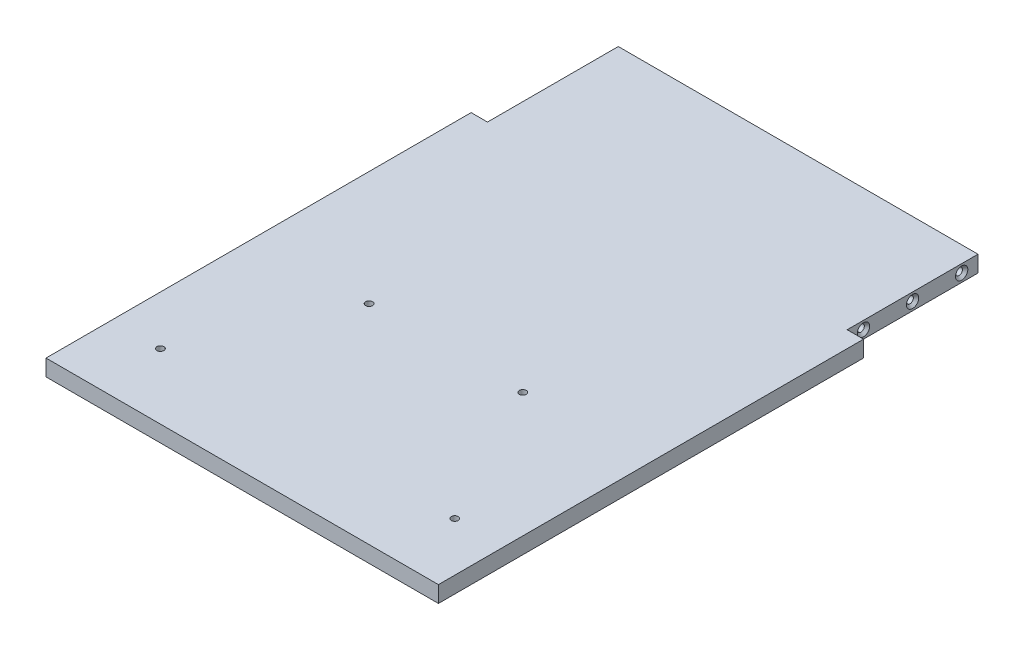
SolidWorks part; units mm, degrees
ref_plane "Front Plane" through (0, 0, 0) normal (0, 0, 1) x (1, 0, 0)
ref_plane "Top Plane" through (0, 0, 0) normal (0, 1, 0) x (1, 0, 0)
ref_plane "Right Plane" through (0, 0, 0) normal (1, 0, 0) x (0, 0, -1)
sketch "Sketch1" plane through (0, 0, 0) normal (0, 1, 0) x (1, 0, 0)
  line L0 (-6.35, 0) -> (-6.35, -50.8)
  line L1 (-6.35, 0) -> (-146.05, 0)
  line L2 (0, -50.8) -> (0, -215.9)
  line L3 (0, -215.9) -> (-152.4, -215.9)
  line L4 (-152.4, -50.8) -> (-152.4, -215.9)
  line L5 (-6.35, -50.8) -> (0, -50.8)
  line L6 (-146.05, 0) -> (-146.05, -50.8)
  line L7 (-146.05, -50.8) -> (-152.4, -50.8)
  point P7 (-3.175, -50.8)
  dimension "D1" = 152.4
  dimension "D2" = 215.9
  dimension "D3" = 50.8
  dimension "D4" = 6.35
  dimension "D5" = 6.35
  dimension "D6" = 50.8
extrude "Boss-Extrude1" add sketch "Sketch1" along normal blind 6.35
sketch "Sketch2" plane through (-6.35, 0, 0) normal (1, 0, 0) x (0, 0, -1)
  line L0 (-50.8, 6.35) -> (-50.8, 0) construction
  line L1 (-50.8, 6.35) -> (-50.8, 0) construction
  line L2 (-50.8, 0) -> (0, 0) construction
  circle A0 centre (-44.45, 3.175) radius 1.8288
  circle A1 centre (-25.4, 3.175) radius 1.8288
  circle A2 centre (-6.35, 3.175) radius 1.8288
  dimension "D4" = 3.175
  dimension "D5" = 3.175
  dimension "D6" = 3.6576
  dimension "D7" = 3.6576
  dimension "D8" = 3.6576
  dimension "D1" = 6.35
  dimension "D2" = 25.4
  dimension "D3" = 44.45
hole_wizard "#6-32 Tapped Hole1" positions "Sketch3" profile "Sketch4" tap size "#6-32" standard "ANSI Inch"
sketch "Sketch3" plane through (-6.35, 0, 0) normal (1, 0, 0) x (0, 0, -1)
  point P0 (-44.45, 3.175)
  point P3 (-25.4, 3.175)
  point P6 (-6.35, 3.175)
sketch "Sketch4" plane through (-6.35, 3.175, 44.45) normal (0, 1, 0) x (0, 0, -1)
  line L0 (0, 0) -> (0, 12.7)
  line L1 (0, 12.7) -> (1.3525, 11.8873)
  line L2 (1.3525, 11.8873) -> (1.3525, 1.0351)
  line L3 (1.3525, 1.0351) -> (2.3876, 0)
  line L5 (2.3876, 0) -> (0, 0)
  line L6 (-1.3525, 1.0351) -> (-2.3876, 0) construction
  line L10 (0, 12.7) -> (-1.3526, 11.8873) construction
  line L11 (0, -6.35) -> (0, 107.95) construction
  dimension "Tap Drill Dia." = 2.7051
  dimension "Tap Drill Depth" = 12.7
  dimension "Near C'Sink Dia." = 4.7752
  dimension "Near C'Sink Angle" = 90
  dimension "Drill Angle" = 118
cosmetic thread "Hole Thread1"
cosmetic thread "Hole Thread2"
cosmetic thread "Hole Thread3"
sketch "Sketch5" plane through (-146.05, 0, 0) normal (-1, 0, 0) x (0, 0, 1)
  circle A0 centre (6.35, 3.175) radius 1.8288
  circle A1 centre (25.4, 3.175) radius 1.8288
  circle A2 centre (44.45, 3.175) radius 1.8288
  dimension "D1" = 3.6576
  dimension "D2" = 3.6576
  dimension "D3" = 3.6576
hole_wizard "#6-32 Tapped Hole2" positions "Sketch6" profile "Sketch7" tap size "#6-32" standard "ANSI Inch"
sketch "Sketch6" plane through (-146.05, 0, 0) normal (-1, 0, 0) x (0, 0, 1)
  point P0 (6.35, 3.175)
  point P3 (25.4, 3.175)
  point P6 (44.45, 3.175)
sketch "Sketch7" plane through (-146.05, 3.175, 6.35) normal (0, 1, 0) x (0, 0, 1)
  line L0 (0, 0) -> (0, 12.7)
  line L1 (0, 12.7) -> (1.3525, 11.8873)
  line L2 (1.3525, 11.8873) -> (1.3525, 1.0351)
  line L3 (1.3525, 1.0351) -> (2.3876, 0)
  line L5 (2.3876, 0) -> (0, 0)
  line L6 (-1.3525, 1.0351) -> (-2.3876, 0) construction
  line L10 (0, 12.7) -> (-1.3526, 11.8873) construction
  line L11 (0, -6.35) -> (0, 107.95) construction
  dimension "Tap Drill Dia." = 2.7051
  dimension "Tap Drill Depth" = 12.7
  dimension "Near C'Sink Dia." = 4.7752
  dimension "Near C'Sink Angle" = 90
  dimension "Drill Angle" = 118
cosmetic thread "Hole Thread4"
cosmetic thread "Hole Thread5"
cosmetic thread "Hole Thread6"
sketch "Sketch8" plane through (0, 6.35, 0) normal (0, 1, 0) x (1, 0, 0)
  line L0 (0, -215.9) -> (0, -50.8) construction
  line L1 (-152.4, -215.9) -> (0, -215.9) construction
  circle A0 centre (-48.26, -134.874) radius 1.8288
  circle A1 centre (-107.95, -134.874) radius 1.8288
  dimension "D1" = 48.26
  dimension "D2" = 81.026
  dimension "D3" = 59.69
  dimension "D4" = 81.026
  dimension "D5" = 3.6576
  dimension "D6" = 3.6576
sketch "Sketch9" plane through (0, 6.35, 0) normal (0, 1, 0) x (1, 0, 0)
  line L0 (-152.4, -215.9) -> (0, -215.9) construction
  line L1 (-152.4, -50.8) -> (-152.4, -215.9) construction
  circle A0 centre (-133.35, -190.5) radius 1.8288
  circle A1 centre (-19.05, -190.5) radius 1.8288
  dimension "D1" = 114.3
  dimension "D2" = 25.4
  dimension "D3" = 19.05
  dimension "D4" = 3.6576
  dimension "D5" = 3.6576
hole_wizard "#6-32 Tapped Hole3" positions "Sketch12" profile "Sketch13" tap size "#6-32" standard "ANSI Inch" end condition up to next
sketch "Sketch12" plane through (0, 6.35, 0) normal (0, 1, 0) x (1, 0, 0)
  point P0 (-133.35, -190.5)
  point P3 (-19.05, -190.5)
sketch "Sketch13" plane through (-133.35, 6.35, 190.5) normal (1, 0, 0) x (0, 0, 1)
  line L0 (0, 0) -> (0, 6.35)
  line L1 (0, 6.35) -> (1.3525, 6.35)
  line L2 (1.3525, 6.35) -> (1.3525, 0)
  line L5 (1.3525, 0) -> (0, 0)
  line L11 (0, -6.35) -> (0, 107.95) construction
  dimension "Thru Tap Drill Dia." = 2.7051
  dimension "Thru Tap Drill Depth" = 6.35
cosmetic thread "Hole Thread7"
cosmetic thread "Hole Thread8"
hole_wizard "#6-32 Tapped Hole4" positions "Sketch14" profile "Sketch15" tap size "#6-32" standard "ANSI Inch" end condition up to next
sketch "Sketch14" plane through (0, 6.35, 0) normal (0, 1, 0) x (1, 0, 0)
  point P0 (-107.95, -134.874)
  point P3 (-48.26, -134.874)
sketch "Sketch15" plane through (-107.95, 6.35, 134.874) normal (1, 0, 0) x (0, 0, 1)
  line L0 (0, 0) -> (0, 6.35)
  line L1 (0, 6.35) -> (1.3525, 6.35)
  line L2 (1.3525, 6.35) -> (1.3525, 0)
  line L5 (1.3525, 0) -> (0, 0)
  line L11 (0, -6.35) -> (0, 107.95) construction
  dimension "Thru Tap Drill Dia." = 2.7051
  dimension "Thru Tap Drill Depth" = 6.35
cosmetic thread "Hole Thread9"
cosmetic thread "Hole Thread10"
